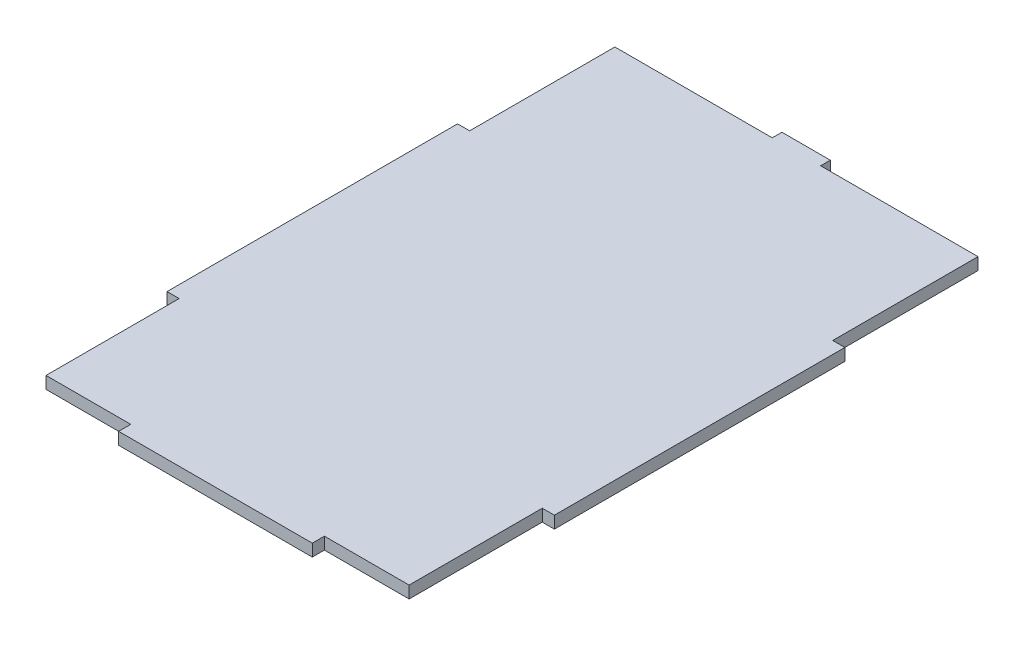
SolidWorks part; units mm, degrees
ref_plane "Front Plane" through (0, 0, 0) normal (0, 0, 1) x (1, 0, 0)
ref_plane "Top Plane" through (0, 0, 0) normal (0, 1, 0) x (1, 0, 0)
ref_plane "Right Plane" through (0, 0, 0) normal (1, 0, 0) x (0, 0, -1)
sketch "Sketch1" plane through (0, 0, 0) normal (0, 1, 0) x (1, 0, 0)
  line L1 (-30.9107, -111.4813) -> (172.2893, -111.4813)
  line L2 (-30.9107, -111.4813) -> (-30.9107, 193.3187)
  line L3 (-30.9107, 193.3187) -> (172.2893, 193.3187)
  line L4 (172.2893, -111.4813) -> (172.2893, 193.3187)
  dimension "D1" = 203.2
  dimension "D2" = 304.8
extrude "Boss-Extrude1" add sketch "Sketch1" along normal blind 6.35
sketch "Sketch2" plane through (0, 6.35, 0) normal (0, 1, 0) x (1, 0, 0)
  line L1 (-30.9107, -111.4813) -> (-24.5607, -111.4813)
  line L2 (-30.9107, -111.4813) -> (-30.9107, -35.2813)
  line L3 (-30.9107, -35.2813) -> (-24.5607, -35.2813)
  line L4 (-24.5607, -111.4813) -> (-24.5607, -35.2813)
  line L5 (-30.9107, 193.3187) -> (-24.5607, 193.3187)
  line L6 (-30.9107, 193.3187) -> (-30.9107, 117.1187)
  line L7 (-30.9107, 117.1187) -> (-24.5607, 117.1187)
  line L8 (-24.5607, 193.3187) -> (-24.5607, 117.1187)
  line L9 (172.2893, 193.3187) -> (165.9393, 193.3187)
  line L10 (172.2893, 193.3187) -> (172.2893, 117.1187)
  line L11 (172.2893, 117.1187) -> (165.9393, 117.1187)
  line L12 (165.9393, 193.3187) -> (165.9393, 117.1187)
  line L13 (172.2893, -111.4813) -> (165.9393, -111.4813)
  line L14 (172.2893, -111.4813) -> (172.2893, -35.2813)
  line L15 (172.2893, -35.2813) -> (165.9393, -35.2813)
  line L16 (165.9393, -111.4813) -> (165.9393, -35.2813)
  dimension "D1" = 76.2
  dimension "D2" = 6.35
  dimension "D3" = 76.2
  dimension "D4" = 6.35
  dimension "D5" = 6.35
  dimension "D6" = 6.35
  dimension "D7" = 76.2
  dimension "D8" = 76.2
extrude "Cut-Extrude1" cut sketch "Sketch2" against normal blind 6.35
sketch "Sketch3" plane through (0, 6.35, 0) normal (0, 1, 0) x (1, 0, 0)
  line L0 (165.9393, 193.3187) -> (-24.5607, 193.3187) construction
  line L1 (57.9893, 193.3187) -> (83.3893, 193.3187)
  line L2 (57.9893, 193.3187) -> (57.9893, 198.3987)
  line L3 (57.9893, 198.3987) -> (83.3893, 198.3987)
  line L4 (83.3893, 193.3187) -> (83.3893, 198.3987)
  line L5 (-30.9107, 117.1187) -> (-30.9107, -35.2813) construction
  line L6 (172.2893, -35.2813) -> (172.2893, 117.1187) construction
  point P8 (83.3893, 195.8587)
  dimension "D1" = 88.9
  dimension "D2" = 88.9
  dimension "D3" = 5.08
extrude "Boss-Extrude3" add sketch "Sketch3" against normal blind 6.35
sketch "Sketch5" plane through (0, 6.35, 0) normal (0, 1, 0) x (1, 0, 0)
  line L1 (-24.5607, -111.4813) -> (19.8893, -111.4813)
  line L2 (-24.5607, -111.4813) -> (-24.5607, -105.1313)
  line L3 (-24.5607, -105.1313) -> (19.8893, -105.1313)
  line L4 (19.8893, -111.4813) -> (19.8893, -105.1313)
  line L5 (165.9393, -111.4813) -> (121.4893, -111.4813)
  line L6 (165.9393, -111.4813) -> (165.9393, -105.1313)
  line L7 (165.9393, -105.1313) -> (121.4893, -105.1313)
  line L8 (121.4893, -111.4813) -> (121.4893, -105.1313)
  dimension "D1" = 6.35
  dimension "D2" = 101.6
  dimension "D3" = 44.45
  dimension "D4" = 44.45
extrude "Cut-Extrude2" cut sketch "Sketch5" against normal blind 6.35
